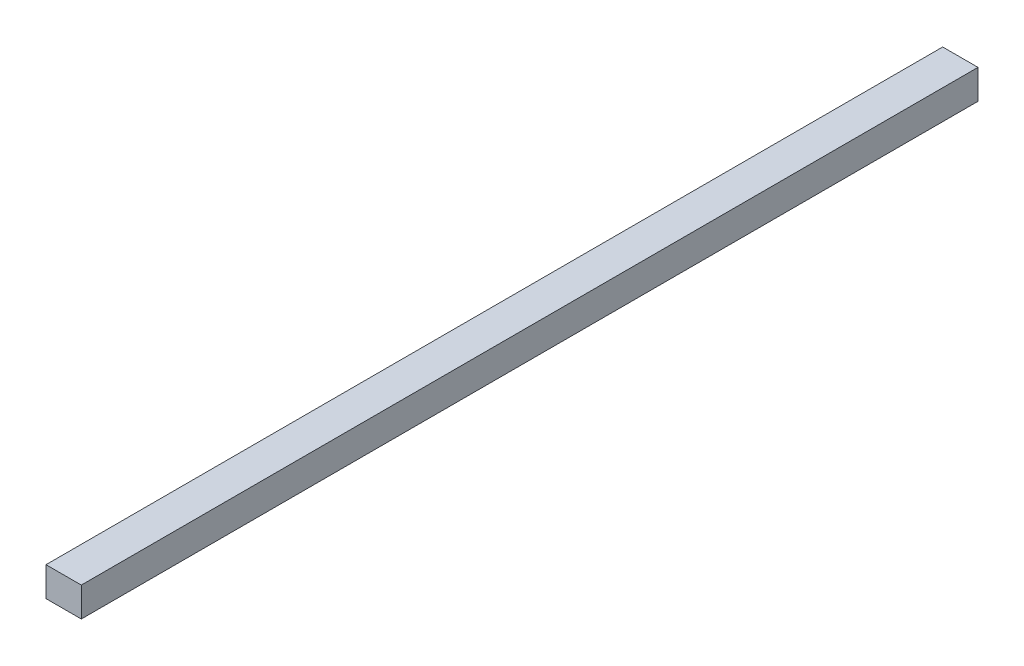
SolidWorks part; units mm, degrees
ref_plane "Front Plane" through (0, 0, 0) normal (0, 0, 1) x (1, 0, 0)
ref_plane "Top Plane" through (0, 0, 0) normal (0, 1, 0) x (1, 0, 0)
ref_plane "Right Plane" through (0, 0, 0) normal (1, 0, 0) x (0, 0, -1)
sketch "Sketch1" plane through (0, 0, 0) normal (0, 0, 1) x (1, 0, 0)
  line L0 (-6, 0) -> (6, 0) construction
  line L1 (0, -5) -> (0, 5) construction
  line L5 (-6, 5) -> (6, 5) construction
  line L7 (-6, 5) -> (-6, -5) construction
  line L8 (6, -5) -> (6, 5) construction
  line L13 (-6, -5) -> (6, -5) construction
  point P0 (0, 0)
  point P4 (0, 0)
  point P9 (0, 0)
  point P22 (0, 5)
  dimension "Thickness" = 10
  dimension "D1" = 12
sketch "Sketch2" plane through (0, 0, 0) normal (0, 1, 0) x (0, 0, -1)
  line L0 (152.4, 0) -> (-152.4, 0) construction
  line L2 (-152.4, 6) -> (152.4, 6) construction
  line L3 (-152.4, 6) -> (-152.4, -6) construction
  line L4 (-152.4, -6) -> (152.4, -6) construction
  line L5 (152.4, 6) -> (152.4, -6) construction
  line L6 (-152.4, 6) -> (152.4, -6) construction
  line L7 (-152.4, -6) -> (152.4, 6) construction
  point P4 (0, 0)
  point P7 (0, 0)
  point P12 (-138.6, 6)
  point P13 (138.6, 6)
  dimension "Length" = 304.8
  dimension "Width" = 12
  dimension "D1" = 13.8
  dimension "D2" = 13.8
sketch "Sketch3" plane through (0, 0, 0) normal (0, 0, 1) x (1, 0, 0)
  line L3 (-6, 5) -> (6, 5)
  line L17 (6, 5) -> (6, -5)
  line L18 (6, -5) -> (-6, -5)
  line L19 (-6, -5) -> (-6, 5)
extrude "Boss-Extrude1" add sketch "Sketch3" along normal mid plane 304.8
equation "\"D1@Boss-Extrude1\" = \"Length@Sketch2\""
equation "\"D1@Sketch1\"=\"Width@Sketch2\""
equation "\"D1@Sketch2\"=\"Width@Sketch2\"*1.15"
equation "\"D2@Sketch2\"=\"D1@Sketch2\""
